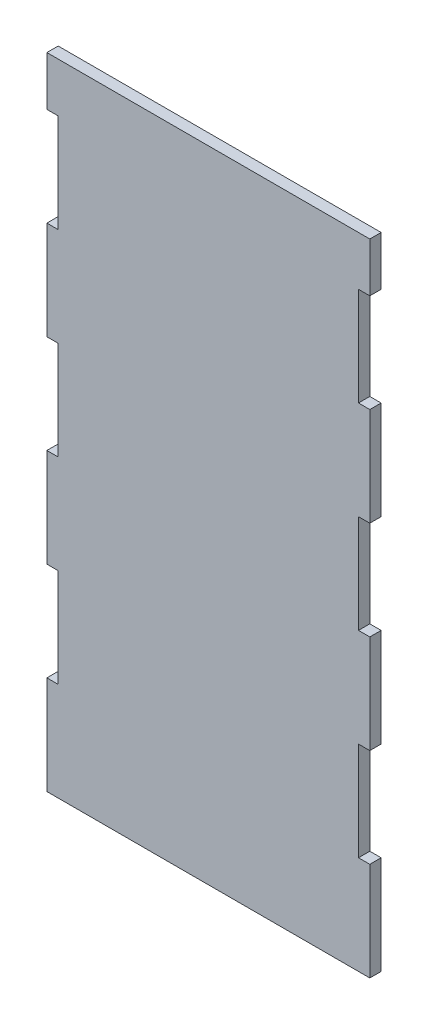
SolidWorks part; units mm, degrees
ref_plane "Front Plane" through (0, 0, 0) normal (0, 0, 1) x (1, 0, 0)
ref_plane "Top Plane" through (0, 0, 0) normal (0, 1, 0) x (1, 0, 0)
ref_plane "Right Plane" through (0, 0, 0) normal (1, 0, 0) x (0, 0, -1)
sketch "Sketch1" plane through (0, 0, 0) normal (0, 0, 1) x (1, 0, 0)
  line L1 (-41.656, 82.55) -> (41.656, 82.55)
  line L2 (-41.656, 82.55) -> (-41.656, -82.55)
  line L3 (-41.656, -82.55) -> (41.656, -82.55)
  line L4 (41.656, 82.55) -> (41.656, -82.55)
  point P4 (0, 82.55)
  point P6 (-41.656, 0)
  dimension "D1" = 83.312
  dimension "D2" = 165.1
extrude "Boss-Extrude1" add sketch "Sketch1" along normal mid plane 2.921
sketch "Sketch2" plane through (0, 0, 1.4605) normal (0, 0, 1) x (1, 0, 0)
  line L0 (-38.735, -82.55) -> (38.735, -82.55)
  line L1 (-41.656, 82.55) -> (41.656, 82.55)
  line L2 (-41.656, 82.55) -> (-41.656, -82.55)
  line L3 (-41.656, -82.55) -> (-38.735, -82.55)
  line L4 (41.656, 82.55) -> (41.656, -82.55)
  line L5 (38.735, -82.55) -> (41.656, -82.55)
  line L6 (-41.656, 82.55) -> (-38.735, 82.55)
  line L7 (-41.656, 82.55) -> (-41.656, -82.55)
  line L8 (-41.656, -82.55) -> (-38.735, -82.55)
  line L9 (-38.735, 82.55) -> (-38.735, -82.55)
  line L10 (41.656, 82.55) -> (38.735, 82.55)
  line L11 (41.656, 82.55) -> (41.656, -82.55)
  line L12 (41.656, -82.55) -> (38.735, -82.55)
  line L13 (38.735, 82.55) -> (38.735, -82.55)
  line L14 (-41.656, -57.15) -> (-38.735, -57.15)
  line L15 (38.735, -57.15) -> (41.656, -57.15)
  line L16 (-41.656, -31.75) -> (-38.735, -31.75)
  line L17 (38.735, -31.75) -> (41.656, -31.75)
  line L18 (-41.656, -6.35) -> (-38.735, -6.35)
  line L19 (38.735, -6.35) -> (41.656, -6.35)
  line L20 (-41.656, 19.05) -> (-38.735, 19.05)
  line L21 (38.735, 19.05) -> (41.656, 19.05)
  line L22 (-41.656, 44.45) -> (-38.735, 44.45)
  line L23 (38.735, 44.45) -> (41.656, 44.45)
  line L24 (-41.656, 69.85) -> (-38.735, 69.85)
  line L25 (38.735, 69.85) -> (41.656, 69.85)
  line L26 (-41.656, -82.55) -> (-41.656, -57.15) construction
  dimension "D1" = 2.921
  dimension "D2" = 2.921
  dimension "D4" = 25.4
  dimension "D5" = 2.921
  dimension "D6" = 2.921
  dimension "D3" = 7
extrude "Cut-Extrude1" cut sketch "Sketch2" against normal blind 2.921 contours L24 L7 L22 L9 | L20 L7 L18 L9 | L16 L7 L14 L9 | L17 L13 L15 L11 | L21 L13 L19 L11 | L25 L13 L23 L11
